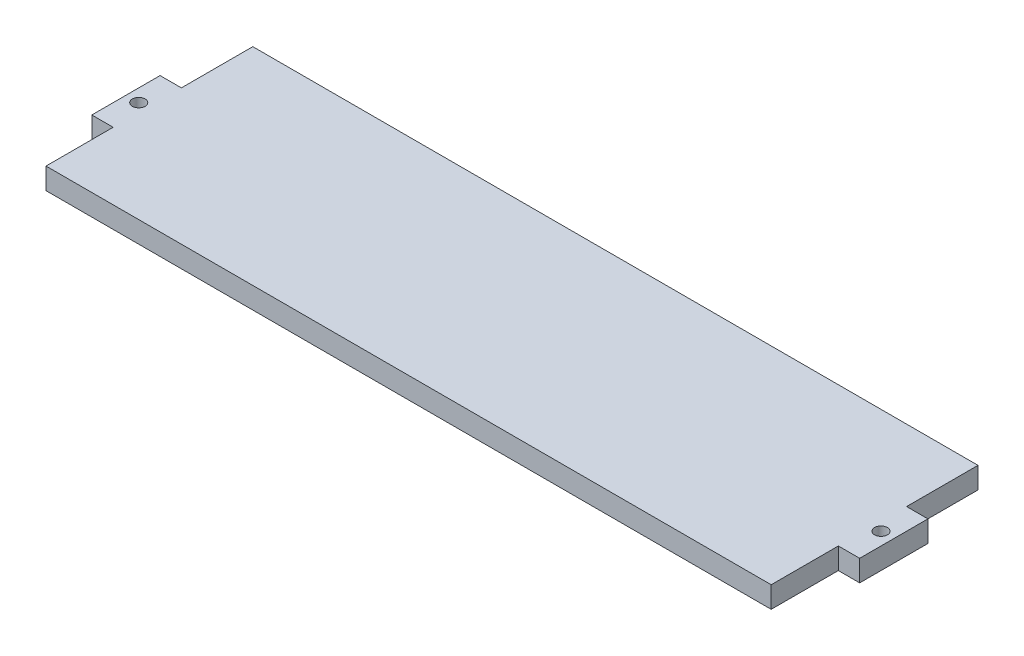
SolidWorks part; units mm, degrees
material "Trupan"
ref_plane "Alzado" through (0, 0, 0) normal (0, 0, 1) x (1, 0, 0)
ref_plane "Planta" through (0, 0, 0) normal (0, 1, 0) x (1, 0, 0)
ref_plane "Vista lateral" through (0, 0, 0) normal (1, 0, 0) x (0, 0, -1)
sketch "Croquis1" plane through (0, 0, 0) normal (0, 1, 0) x (1, 0, 0)
  line L1 (90, -8) -> (-90, -8)
  line L2 (90, -8) -> (90, 8)
  line L3 (90, 8) -> (-90, 8)
  line L4 (-90, -8) -> (-90, 8)
  line L5 (90, -8) -> (-90, 8) construction
  line L6 (90, 8) -> (-90, -8) construction
  point P0 (0, 0)
  dimension "D1" = 16
  dimension "D2" = 180
extrude "Saliente-Extruir1" add sketch "Croquis1" along normal blind 5
sketch "Croquis2" plane through (0, 5, 0) normal (0, 1, 0) x (1, 0, 0)
  line L0 (90, 8) -> (-90, 8) construction
  line L1 (85, 25.74) -> (-85, 25.74)
  line L2 (85, 25.74) -> (85, 8)
  line L3 (85, 8) -> (-85, 8)
  line L4 (-85, 25.74) -> (-85, 8)
  line L5 (85, 25.74) -> (-85, 8) construction
  line L6 (85, 8) -> (-85, 25.74) construction
  line L7 (-90, -8) -> (90, -8) construction
  line L8 (85, -25.74) -> (-85, -25.74)
  line L9 (85, -25.74) -> (85, -8)
  line L10 (85, -8) -> (-85, -8)
  line L11 (-85, -25.74) -> (-85, -8)
  line L12 (85, -25.74) -> (-85, -8) construction
  line L13 (85, -8) -> (-85, -25.74) construction
  point P0 (0, 16.87)
  point P7 (0, -16.87)
  dimension "D1" = 17.74
  dimension "D2" = 170
  dimension "D3" = 17.74
  dimension "D4" = 170
extrude "Saliente-Extruir2" add sketch "Croquis2" against normal blind 5
sketch "Croquis3" plane through (0, 5, 0) normal (0, 1, 0) x (1, 0, 0)
  line L0 (-90, 8) -> (-90, -8) construction
  line L2 (-90, -8) -> (-85, -8) construction
  circle A0 centre (-87, 0) radius 1.5
  dimension "D1" = 3
  dimension "D2" = 3
  dimension "D3" = 8
extrude "Cortar-Extruir1" cut sketch "Croquis3" against normal blind 5
mirror "Simetría1" about plane through (0, 0, 0) normal (1, 0, 0) of "Cortar-Extruir1"
sketch "Croquis4" plane through (0, 5, 0) normal (0, 1, 0) x (1, 0, 0)
  line L0 (85, -25.74) -> (85, -8) construction
  line L1 (-85, -25.74) -> (85, -25.74)
  line L2 (-85, -25.74) -> (-85, -23.74)
  line L3 (-85, -23.74) -> (85, -23.74)
  line L4 (85, -25.74) -> (85, -23.74)
  dimension "D1" = 2
extrude "Cortar-Extruir2" cut sketch "Croquis4" against normal through all
sketch "Croquis5" plane through (0, 5, 0) normal (0, 1, 0) x (1, 0, 0)
  line L0 (85, 8) -> (85, 25.74) construction
  line L1 (-85, 25.74) -> (85, 25.74)
  line L2 (-85, 25.74) -> (-85, 24.74)
  line L3 (-85, 24.74) -> (85, 24.74)
  line L4 (85, 25.74) -> (85, 24.74)
  dimension "D1" = 1
extrude "Cortar-Extruir3" cut sketch "Croquis5" against normal blind 10
